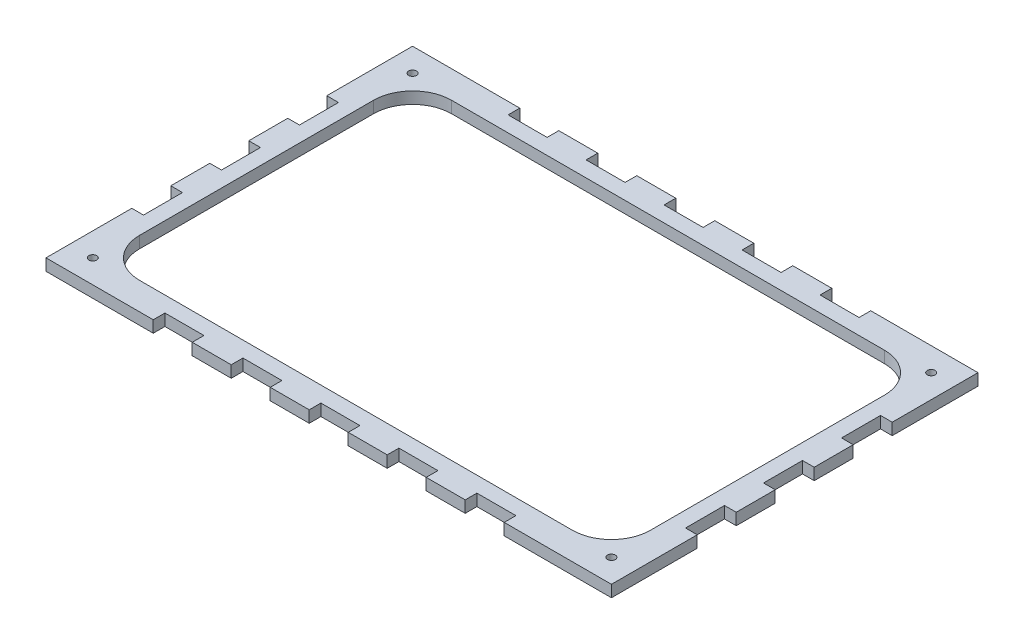
SolidWorks part; units mm, degrees
material "Maple"
ref_plane "Front Plane" through (0, 0, 0) normal (0, 0, 1) x (1, 0, 0)
ref_plane "Top Plane" through (0, 0, 0) normal (0, 1, 0) x (1, 0, 0)
ref_plane "Right Plane" through (0, 0, 0) normal (1, 0, 0) x (0, 0, -1)
sketch "Sketch1" plane through (0, 0, 0) normal (0, 1, 0) x (1, 0, 0)
  line L1 (0, 0) -> (145, 0)
  line L2 (0, 0) -> (0, -94)
  line L3 (0, -94) -> (145, -94)
  line L4 (145, 0) -> (145, -94)
  dimension "D1" = 145
  dimension "D2" = 94
extrude "Boss-Extrude1" add sketch "Sketch1" along normal blind 3
sketch "Sketch2" plane through (0, 3, 0) normal (0, 1, 0) x (1, 0, 0)
  line L0 (145, 0) -> (0, 0) construction
  line L1 (7, -7) -> (138, -7)
  line L2 (7, -7) -> (7, -87)
  line L3 (7, -87) -> (138, -87)
  line L4 (138, -7) -> (138, -87)
  line L5 (0, -94) -> (145, -94) construction
  line L6 (0, 0) -> (0, -94) construction
  line L7 (145, -94) -> (145, 0) construction
  dimension "D1" = 7
  dimension "D2" = 7
  dimension "D3" = 7
  dimension "D4" = 7
extrude "Cut-Extrude1" cut sketch "Sketch2" against normal through all
fillet "Fillet1" radius 10 4 edges at (138, 1.5, 87) (138, 1.5, 7) (7, 1.5, 7) (7, 1.5, 87)
sketch "Sketch3" plane through (0, 0, 0) normal (0, -1, 0) x (1, 0, 0)
  line L0 (145, 0) -> (0, 0) construction
  line L1 (0, 0) -> (0, 94) construction
  line L2 (0, 94) -> (145, 94) construction
  line L3 (145, 94) -> (145, 0) construction
  circle A0 centre (6, 88) radius 1
  circle A1 centre (139, 88) radius 1
  circle A2 centre (139, 6) radius 1
  circle A3 centre (6, 6) radius 1
  dimension "D1" = 2
  dimension "D2" = 2
  dimension "D3" = 2
  dimension "D4" = 2
  dimension "D5" = 6
  dimension "D6" = 6
  dimension "D7" = 6
  dimension "D8" = 6
  dimension "D9" = 6
  dimension "D10" = 6
  dimension "D11" = 6
  dimension "D12" = 6
extrude "Cut-Extrude2" cut sketch "Sketch3" against normal through all
sketch "Sketch8" plane through (0, 0, 0) normal (0, -1, 0) x (-1, 0, 0)
  line L0 (-72.5, -94) -> (-72.5, 0) construction
  line L1 (0, -94) -> (-145, -94) construction
  line L2 (-145, 0) -> (0, 0) construction
  line L4 (-67.5, -94) -> (-77.5, -94)
  line L5 (-67.5, -94) -> (-67.5, -91)
  line L6 (-67.5, -91) -> (-77.5, -91)
  line L7 (-77.5, -94) -> (-77.5, -91)
  line L8 (-67.5, -94) -> (-77.5, -91) construction
  line L9 (-67.5, -91) -> (-77.5, -94) construction
  line L10 (-67.5, -3) -> (-77.5, -3)
  line L11 (-67.5, -3) -> (-67.5, 0)
  line L12 (-67.5, 0) -> (-77.5, 0)
  line L13 (-77.5, -3) -> (-77.5, 0)
  line L14 (-67.5, -3) -> (-77.5, 0) construction
  line L15 (-67.5, 0) -> (-77.5, -3) construction
  point P6 (-72.5, -92.5)
  point P11 (-72.5, -1.5)
  dimension "D1" = 3
  dimension "D2" = 10
extrude "Cut-Extrude5" cut sketch "Sketch8" against normal through all
pattern_linear "LPattern3" count 4 spacing 20 along (1, 0, 0) count 4 spacing 20 along (-1, 0, 0) of "Cut-Extrude5"
sketch "Sketch9" plane through (0, 0, 0) normal (0, -1, 0) x (-1, 0, 0)
  line L0 (0, -47) -> (-145, -47) construction
  line L1 (0, 0) -> (0, -94) construction
  line L2 (-145, -94) -> (-145, 0) construction
  line L4 (0, -52) -> (-3, -52)
  line L5 (0, -52) -> (0, -42)
  line L6 (0, -42) -> (-3, -42)
  line L7 (-3, -52) -> (-3, -42)
  line L8 (0, -52) -> (-3, -42) construction
  line L9 (0, -42) -> (-3, -52) construction
  line L10 (-142, -52) -> (-145, -52)
  line L11 (-142, -52) -> (-142, -42)
  line L12 (-142, -42) -> (-145, -42)
  line L13 (-145, -52) -> (-145, -42)
  line L14 (-142, -52) -> (-145, -42) construction
  line L15 (-142, -42) -> (-145, -52) construction
  point P6 (-1.5, -47)
  point P11 (-143.5, -47)
  dimension "D1" = 3
  dimension "D2" = 10
extrude "Cut-Extrude6" cut sketch "Sketch9" against normal through all
pattern_linear "LPattern4" count 3 spacing 20 along (0, 0, 1) count 3 spacing 20 along (0, 0, -1) of "Cut-Extrude6"
sketch "Sketch11" plane through (0, 0, 0) normal (0, -1, 0) x (-1, 0, 0)
  line L1 (-145, -82) -> (-142, -82)
  line L2 (-145, -82) -> (-145, -92)
  line L3 (-145, -92) -> (-142, -92)
  line L4 (-142, -82) -> (-142, -92)
  line L5 (-127.5, -94) -> (-137.5, -94)
  line L6 (-127.5, -94) -> (-127.5, -91)
  line L7 (-127.5, -91) -> (-137.5, -91)
  line L8 (-137.5, -94) -> (-137.5, -91)
  line L9 (-127.5, 0) -> (-137.5, 0)
  line L10 (-127.5, 0) -> (-127.5, -3)
  line L11 (-127.5, -3) -> (-137.5, -3)
  line L12 (-137.5, 0) -> (-137.5, -3)
  line L13 (-145, -12) -> (-142, -12)
  line L14 (-145, -12) -> (-145, -2)
  line L15 (-145, -2) -> (-142, -2)
  line L16 (-142, -12) -> (-142, -2)
  line L17 (0, -12) -> (-3, -12)
  line L18 (0, -12) -> (0, -2)
  line L19 (0, -2) -> (-3, -2)
  line L20 (-3, -12) -> (-3, -2)
  line L21 (-17.5, -3) -> (-7.5, -3)
  line L22 (-17.5, -3) -> (-17.5, 0)
  line L23 (-17.5, 0) -> (-7.5, 0)
  line L24 (-7.5, -3) -> (-7.5, 0)
  line L25 (0, -92) -> (-3, -92)
  line L26 (0, -92) -> (0, -82)
  line L27 (0, -82) -> (-3, -82)
  line L28 (-3, -92) -> (-3, -82)
  line L29 (-17.5, -94) -> (-7.5, -94)
  line L30 (-17.5, -94) -> (-17.5, -91)
  line L31 (-17.5, -91) -> (-7.5, -91)
  line L32 (-7.5, -94) -> (-7.5, -91)
extrude "Boss-Extrude4" add sketch "Sketch11" against normal through all
equation "\"D2@Sketch2\"=\"D1@Sketch2\""
equation "\"D3@Sketch2\"=\"D1@Sketch2\""
equation "\"D4@Sketch2\"=\"D1@Sketch2\""
equation "\"D2@Sketch3\"=\"D1@Sketch3\""
equation "\"D3@Sketch3\"=\"D1@Sketch3\""
equation "\"D4@Sketch3\"=\"D1@Sketch3\""
equation "\"D7@Sketch3\"=\"D6@Sketch3\""
equation "\"D8@Sketch3\"=\"D7@Sketch3\""
equation "\"D9@Sketch3\"=\"D5@Sketch3\""
equation "\"D10@Sketch3\"=\"D6@Sketch3\""
equation "\"D11@Sketch3\"=\"D7@Sketch3\""
equation "\"D12@Sketch3\"=\"D8@Sketch3\""
